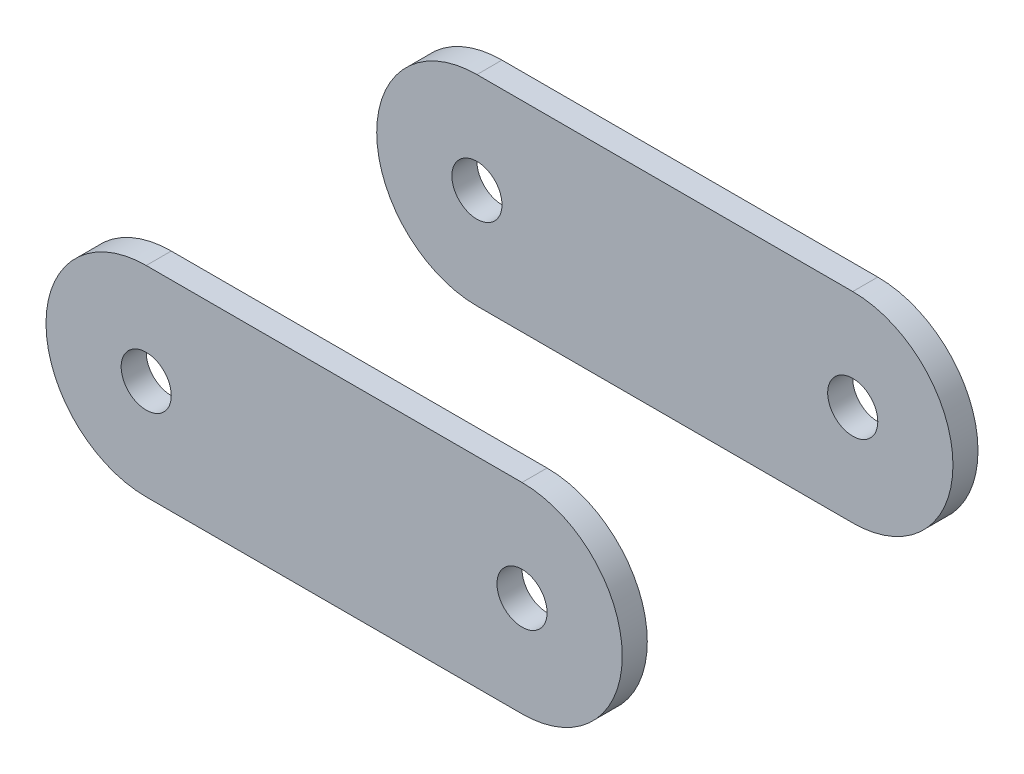
SolidWorks part; units mm, degrees
ref_plane "Plan de face" through (0, 0, 0) normal (0, 0, 1) x (1, 0, 0)
ref_plane "Plan de dessus" through (0, 0, 0) normal (0, 1, 0) x (1, 0, 0)
ref_plane "Plan de droite" through (0, 0, 0) normal (1, 0, 0) x (0, 0, -1)
sketch "Esquisse1" plane through (0, 0, 0) normal (0, 0, 1) x (1, 0, 0)
  line L0 (0, 0) -> (75, 0)
  line L1 (0, 40) -> (75, 40)
  arc A0 (0, 0) -> (0, 40) centre (0, 20) cw
  arc A1 (75, 0) -> (75, 40) centre (75, 20) ccw
  circle A2 centre (0, 20) radius 5
  circle A3 centre (75, 20) radius 5
  dimension "D1" = 75
extrude "Boss.-Extru.1" add sketch "Esquisse1" along normal blind 5
pattern_linear "Répétition linéaire1" count 2 spacing 66 along (0, 0, -1) of "Boss.-Extru.1"
